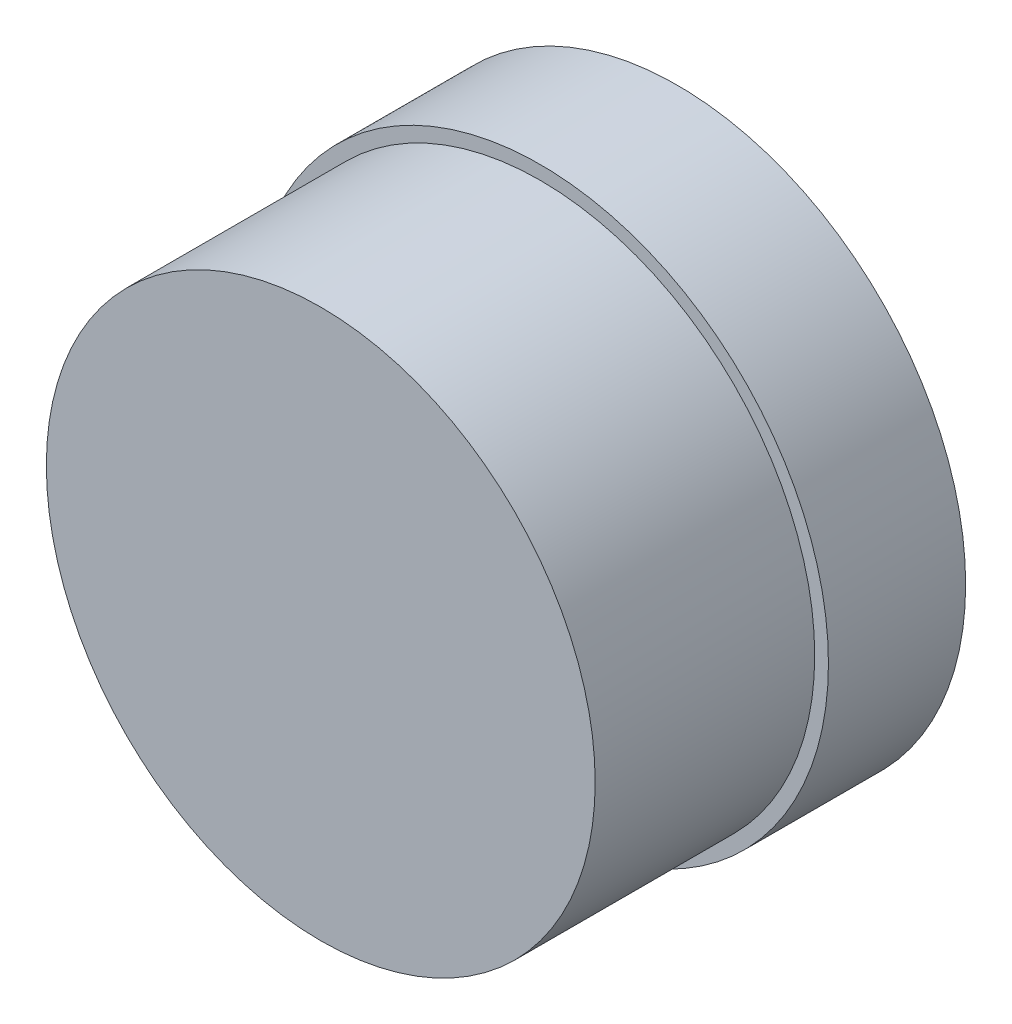
SolidWorks part; units mm, degrees
ref_plane "Front Plane" through (0, 0, 0) normal (0, 0, 1) x (1, 0, 0)
ref_plane "Top Plane" through (0, 0, 0) normal (0, 1, 0) x (1, 0, 0)
ref_plane "Right Plane" through (0, 0, 0) normal (1, 0, 0) x (0, 0, -1)
sketch "Sketch1" plane through (0, 0, 0) normal (0, 0, 1) x (1, 0, 0)
  circle A0 centre (0, 0) radius 10.5
  dimension "D1" = 21
extrude "Boss-Extrude1" add sketch "Sketch1" along normal blind 5
sketch "Sketch2" plane through (0, 0, 5) normal (0, 0, 1) x (1, 0, 0)
  circle A0 centre (0, 0) radius 10
  dimension "D1" = 20
extrude "Boss-Extrude2" add sketch "Sketch2" along normal blind 8
